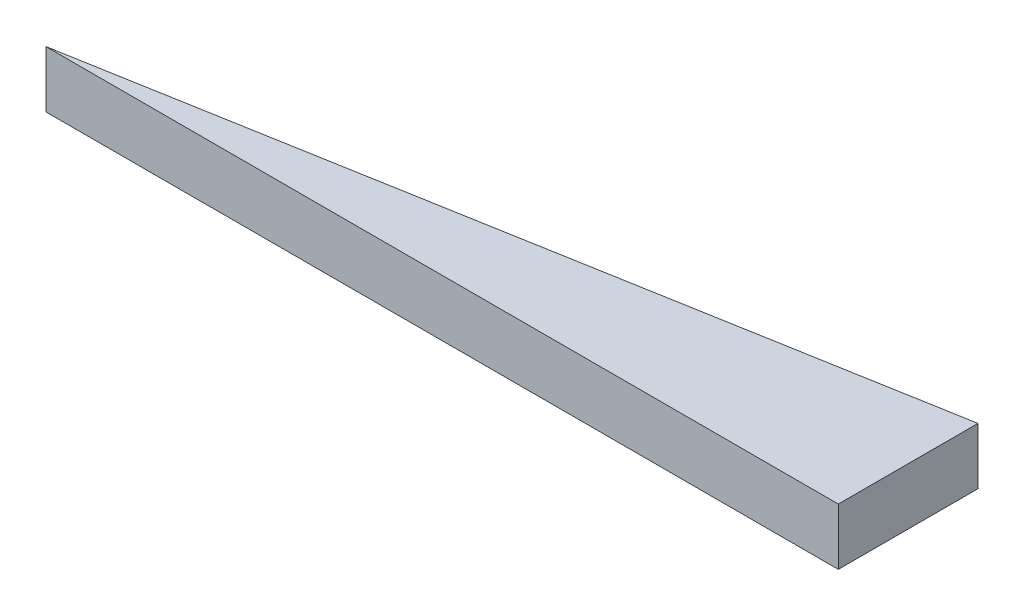
SolidWorks part; units mm, degrees
ref_plane "Front Plane" through (0, 0, 0) normal (0, 0, 1) x (1, 0, 0)
ref_plane "Top Plane" through (0, 0, 0) normal (0, 1, 0) x (1, 0, 0)
ref_plane "Right Plane" through (0, 0, 0) normal (1, 0, 0) x (0, 0, -1)
sketch "Sketch1" plane through (0, 0, 0) normal (0, 1, 0) x (1, 0, 0)
  line L0 (0, 0) -> (177.8, 0)
  line L1 (177.8, 0) -> (177.8, 31.3509)
  line L2 (177.8, 31.3509) -> (0, 0)
  dimension "D1" = 10
  dimension "D2" = 177.8
extrude "Boss-Extrude1" add sketch "Sketch1" along normal blind 12.7
